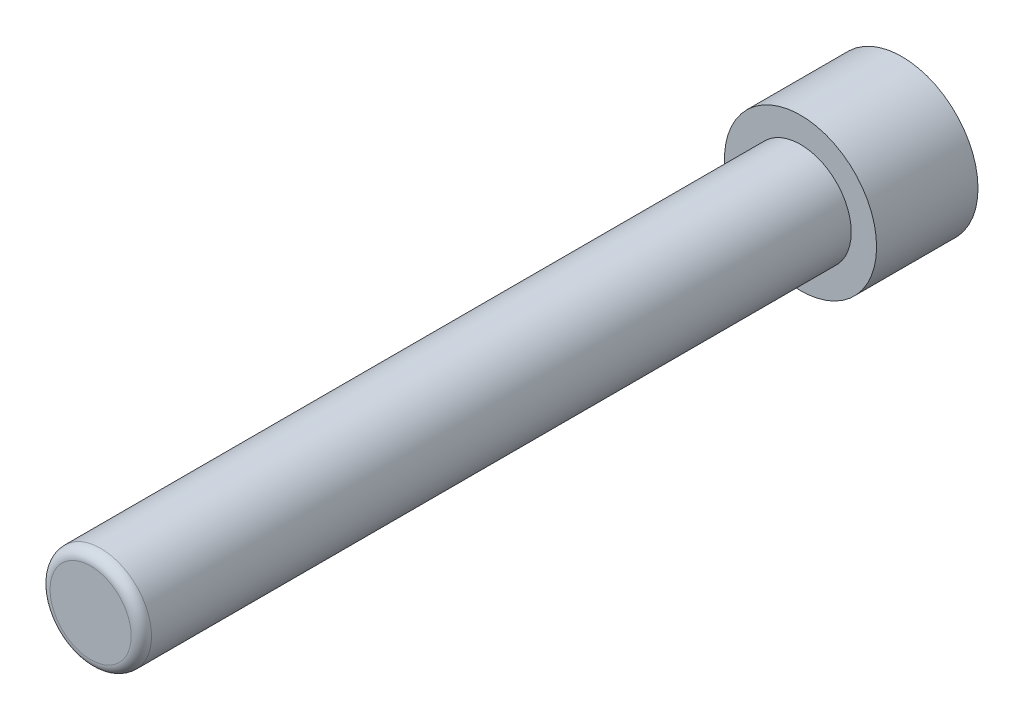
SolidWorks part; units mm, degrees
material "Chrome Stainless Steel"
ref_plane "Front" through (0, 0, 0) normal (0, 0, 1) x (1, 0, 0)
ref_plane "Top" through (0, 0, 0) normal (0, 1, 0) x (1, 0, 0)
ref_plane "Right" through (0, 0, 0) normal (1, 0, 0) x (0, 0, -1)
sketch "Sketch1" plane through (0, 0, 0) normal (0, 0, 1) x (1, 0, 0)
  circle A0 centre (0, 0) radius 19.05
extrude "Extrude1" add sketch "Sketch1" along normal blind 25.4
sketch "Sketch2" plane through (0, 0, 25.4) normal (0, 0, 1) x (1, 0, 0)
  circle A0 centre (0, 0) radius 12.7
extrude "Extrude2" add sketch "Sketch2" along normal blind 177.8
fillet "Fillet1" radius 2.54 1 edges at (12.7, 0, 203.2)
